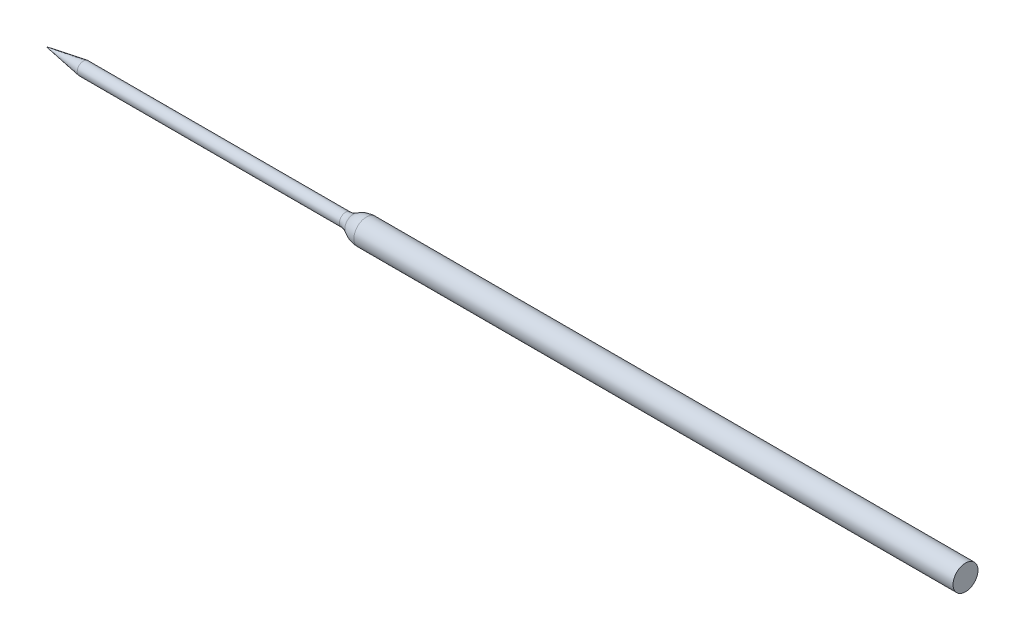
SolidWorks part; units mm, degrees
ref_plane "Front Plane" through (0, 0, 0) normal (0, 0, 1) x (1, 0, 0)
ref_plane "Top Plane" through (0, 0, 0) normal (0, 1, 0) x (1, 0, 0)
ref_plane "Right Plane" through (0, 0, 0) normal (1, 0, 0) x (0, 0, -1)
sketch "Sketch1" plane through (0, 0, 0) normal (0, 0, 1) x (1, 0, 0)
  line L0 (0, 0) -> (4.7625, 0.7937)
  line L1 (4.7625, 0.7937) -> (38.1, 0.7937)
  line L2 (116.9407, 1.5875) -> (116.9407, 0)
  line L3 (40.7407, 1.5875) -> (116.9407, 1.5875)
  line L4 (0, 0) -> (116.9407, 0)
  arc A0 (38.1, 0.7937) -> (39.0934, 1.0923) centre (38.1, 2.5954) ccw
  arc A1 (39.0934, 1.0923) -> (40.7407, 1.5875) centre (40.7407, -1.4003) cw
  dimension "D1" = 0.7937
  dimension "D2" = 1.5875
  dimension "D3" = 4.7625
  dimension "D4" = 38.1
  dimension "D5" = 76.2
revolve "Revolve1" add sketch "Sketch1" angle 360 about L4
